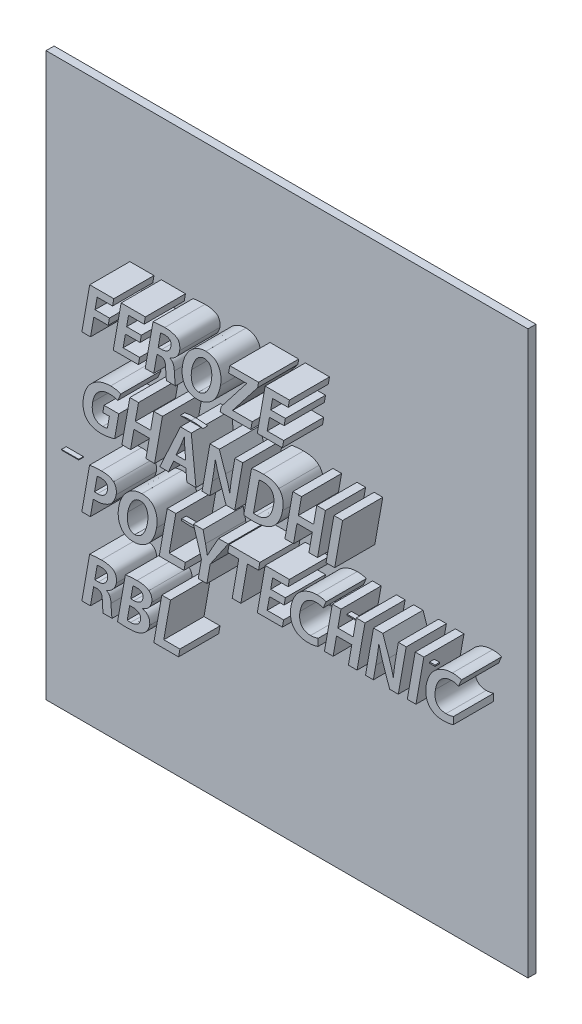
SolidWorks part; units mm, degrees
ref_plane "Front Plane" through (0, 0, 0) normal (0, 0, 1) x (1, 0, 0)
ref_plane "Top Plane" through (0, 0, 0) normal (0, 1, 0) x (1, 0, 0)
ref_plane "Right Plane" through (0, 0, 0) normal (1, 0, 0) x (0, 0, -1)
sketch "Sketch1" plane through (0, 0, 0) normal (0, 0, 1) x (1, 0, 0)
  line L1 (0, 0) -> (120, 0)
  line L2 (0, 0) -> (0, 140)
  line L3 (0, 140) -> (120, 140)
  line L4 (120, 0) -> (120, 140)
  dimension "D1" = 140
  dimension "D2" = 120
extrude "Boss-Extrude1" add sketch "Sketch1" along normal blind 9
sketch "Sketch2" plane through (120, 0, 0) normal (1, 0, 0) x (0, 0, -1)
  line L0 (-9, 0) -> (-9, 140) construction
  line L1 (0, 0) -> (-9, 0)
  line L2 (0, 0) -> (0, 21)
  line L3 (0, 21) -> (-9, 21)
  line L4 (-9, 0) -> (-9, 21)
  line L7 (0, 21) -> (0, 32.5)
  line L9 (17, 21) -> (17, 32.5)
  line L14 (0, 21) -> (17, 21)
  line L15 (0, 21) -> (0, 32.5)
  line L16 (3, 21) -> (17, 21)
  line L17 (17, 21.8213) -> (3.5705, 21.8213)
  line L18 (3.5705, 31.6787) -> (17, 31.6787)
  line L19 (17, 31.6787) -> (17, 32.5)
  line L20 (3, 32.5) -> (17, 32.5)
  arc A0 (3, 32.5) -> (3, 21) centre (6.9939, 26.75) ccw
  arc A1 (3.5705, 31.6787) -> (3.5705, 21.8213) centre (6.9939, 26.75) ccw
  dimension "D5" = 1
  dimension "D1" = 21
  dimension "D2" = 17
  dimension "D3" = 11.5
  dimension "D4" = 3
extrude "Boss-Extrude2" add sketch "Sketch2" against normal blind 120 contours A1 L18 L9 L20 A0 L15 L14 L17
sketch "Sketch3" plane through (0, 0, 0) normal (0, -1, 0) x (1, 0, 0)
  line L17 (0, -17) -> (120, -17) construction
  line L30 (120, 0) -> (95, 0)
  line L31 (120, 0) -> (120, -17)
  line L32 (120, -17) -> (95, -17)
  line L33 (95, 0) -> (95, -17)
  line L35 (0, 0) -> (25, 0)
  line L36 (0, 0) -> (0, -17)
  line L37 (0, -17) -> (25, -17)
  line L38 (25, 0) -> (25, -17)
  line L39 (25, 0) -> (45, 0)
  line L40 (25, 0) -> (25, -17)
  line L41 (25, -17) -> (45, -17)
  line L42 (45, 0) -> (45, -17)
  line L43 (95, 0) -> (75, 0)
  line L44 (95, 0) -> (95, -17)
  line L45 (95, -17) -> (75, -17)
  line L46 (75, 0) -> (75, -17)
  line L47 (45, 0) -> (75, 0)
  line L48 (45, 0) -> (45, -17)
  line L49 (45, -17) -> (75, -17)
  line L50 (75, 0) -> (75, -17)
  line M9 (0, 0) -> (120, 0)
  dimension "D1" = 25
  dimension "D2" = 25
  dimension "D3" = 20
  dimension "D4" = 20
  dimension "D5" = 30
extrude "Cut-Extrude4" cut sketch "Sketch3" against normal blind 120 contours L38 L36 L37 M9 | L33 L32 L31 M9 | L42 L49 L46 M9
sketch "Sketch4" plane through (0, 0, 9) normal (0, 0, 1) x (1, 0, 0)
  text T0 "F G I E T" font "@Adobe Gothic Std B" height in points 72
extrude "Boss-Extrude3" add sketch "Sketch4" along normal blind 1.15
sketch "Sketch5" plane through (0, 0, 9) normal (0, 0, 1) x (1, 0, 0)
  line L1 (0, 140) -> (120, 140)
  line L2 (0, 140) -> (0, 0)
  line L3 (0, 0) -> (120, 0)
  line L4 (120, 140) -> (120, 0)
extrude "Cut-Extrude5" cut sketch "Sketch5" against normal blind 7
sketch "Sketch7" plane through (0, 0, 10.15) normal (0, 0, 1) x (1, 0, 0)
  line L1 (12.0088, 86.188) -> (110.7061, 86.188)
  line L2 (12.0088, 86.188) -> (12.0088, 64.0966)
  line L3 (12.0088, 64.0966) -> (110.7061, 64.0966)
  line L4 (110.7061, 86.188) -> (110.7061, 64.0966)
extrude "Cut-Extrude6" cut sketch "Sketch7" against normal blind 1.4
sketch "Sketch10" plane through (0, 0, 2) normal (0, 0, 1) x (1, 0, 0)
  text T0 "FEROZE \r\nGHANDHI \r\nPOLYTECHNIC\r\nRBL" font "@Adobe Gothic Std B" height in points 36
extrude "Boss-Extrude4" add sketch "Sketch10" along normal blind 10
